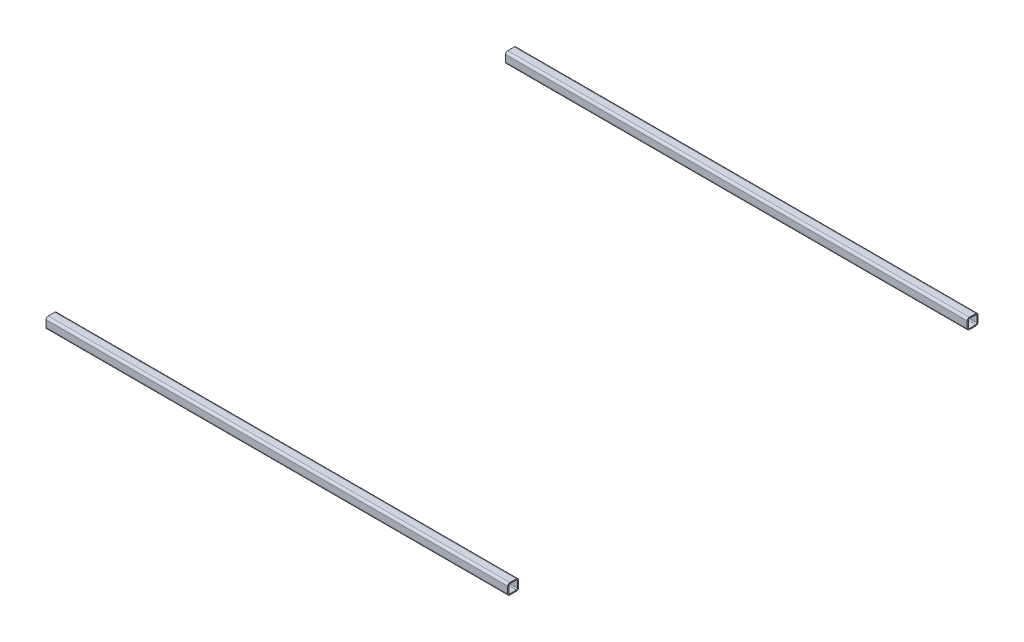
SolidWorks part; units mm, degrees
ref_plane "Front Plane" through (0, 0, 0) normal (0, 0, 1) x (1, 0, 0)
ref_plane "Top Plane" through (0, 0, 0) normal (0, 1, 0) x (1, 0, 0)
ref_plane "Right Plane" through (0, 0, 0) normal (1, 0, 0) x (0, 0, -1)
sketch "Sketch1" plane through (0, 0, 0) normal (0, 1, 0) x (1, 0, 0)
  line L1 (854.075, -850.011) -> (-854.075, -850.011)
  line L2 (854.075, -850.011) -> (854.075, 850.011)
  line L3 (854.075, 850.011) -> (-854.075, 850.011)
  line L4 (-854.075, -850.011) -> (-854.075, 850.011)
  line L5 (854.075, -850.011) -> (-854.075, 850.011) construction
  line L6 (854.075, 850.011) -> (-854.075, -850.011) construction
  point P0 (0, 0)
  dimension "D1" = 1708.15
  dimension "D2" = 1700.022
sketch3d "3DSketch1"
  line L0 (-854.075, 0, -850.011) -> (854.075, 0, -850.011)
  line L1 (854.075, 0, -850.011) -> (854.075, 0, 850.011)
  line L2 (854.075, 0, 850.011) -> (-854.075, 0, 850.011)
  line L3 (-854.075, 0, 850.011) -> (-854.075, 0, -850.011)
other "Square tube 40 X 40 X 4(1)"
ref_plane "Plane2" through (854.075, 0, -850.011) normal (-1, 0, 0) x (0, 0, 1)
sketch "Sketch12" plane through (854.075, 0, -850.011) normal (-1, 0, 0) x (0, 0, 1)
  line L0 (-12, -16) -> (12, -16)
  line L1 (-16, -12) -> (-16, 12)
  line L2 (12, 16) -> (-12, 16)
  line L3 (16, 12) -> (16, -12)
  line L4 (-12, -20) -> (12, -20)
  line L5 (-20, -12) -> (-20, 12)
  line L6 (12, 20) -> (-12, 20)
  line L7 (20, 12) -> (20, -12)
  arc A0 (20, 12) -> (12, 20) centre (12, 12) ccw
  arc A1 (12, -20) -> (20, -12) centre (12, -12) ccw
  arc A2 (-20, -12) -> (-12, -20) centre (-12, -12) ccw
  arc A3 (-12, 20) -> (-20, 12) centre (-12, 12) ccw
  arc A4 (-12, 16) -> (-16, 12) centre (-12, 12) ccw
  arc A5 (16, 12) -> (12, 16) centre (12, 12) ccw
  arc A6 (12, -16) -> (16, -12) centre (12, -12) ccw
  arc A7 (-16, -12) -> (-12, -16) centre (-12, -12) ccw
  point P0 (-20, 0)
  point P1 (20, 0)
  point P2 (0, 20)
  point P3 (0, -20)
  point P4 (0, 0)
  point P5 (-20, -20)
  point P6 (20, -20)
  point P7 (20, 20)
  point P8 (-20, 20)
  point P33 (0, 0)
  dimension "D1" = 8
  dimension "Thickness" = 4
  dimension "V_leg" = 40
